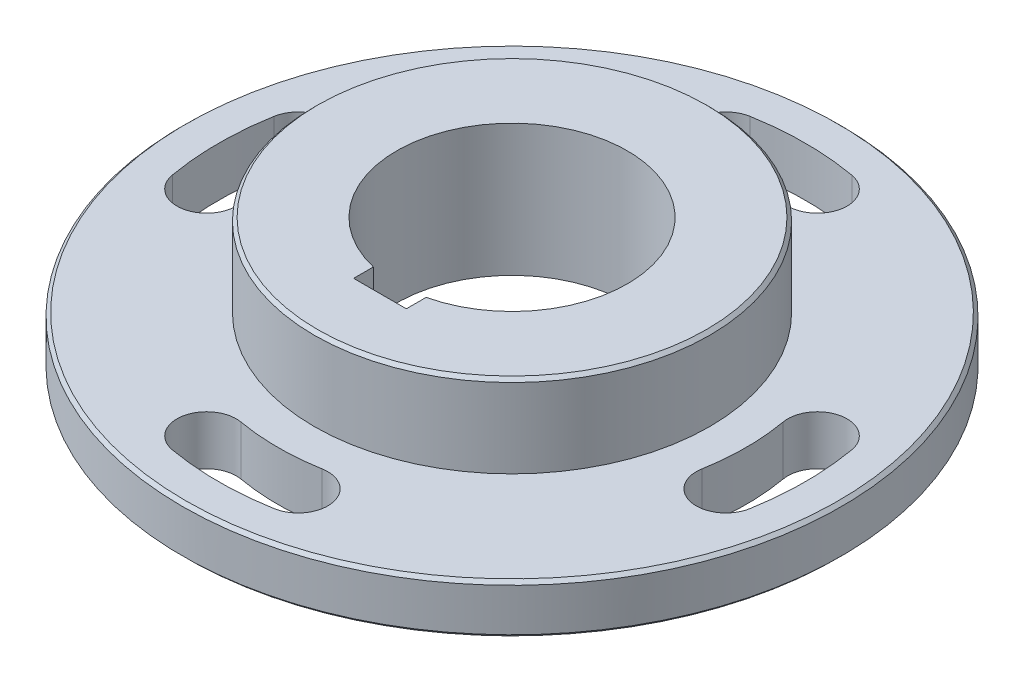
SolidWorks part; units mm, degrees
material "45"
ref_plane "前视基准面" through (0, 0, 0) normal (0, 0, 1) x (1, 0, 0)
ref_plane "上视基准面" through (0, 0, 0) normal (0, 1, 0) x (1, 0, 0)
ref_plane "右视基准面" through (0, 0, 0) normal (1, 0, 0) x (0, 0, -1)
sketch "草图1" plane through (0, 0, 0) normal (0, 0, 1) x (1, 0, 0)
  line L0 (0, 0) -> (0, 222.4832) construction
  line L1 (35, 0) -> (100, 0)
  line L2 (100, 0) -> (100, 15)
  line L3 (100, 15) -> (60, 15)
  line L4 (60, 15) -> (60, 40)
  line L5 (60, 40) -> (35, 40)
  line L6 (35, 40) -> (35, 0)
  dimension "D1" = 200
  dimension "D2" = 15
  dimension "D3" = 70
  dimension "D4" = 40
  dimension "D5" = 120
revolve "旋转1" add sketch "草图1" angle 360 about L0
sketch "草图2" plane through (0, 15, 0) normal (0, 1, 0) x (1, 0, 0)
  line L0 (0, 0) -> (0, 105.9546) construction
  line L1 (0, 0) -> (-18.9336, 107.3776) construction
  line L2 (0, 0) -> (18.7482, 106.3265) construction
  arc A0 (15.4547, 87.6479) -> (-15.4547, 87.6479) centre (0, 0) ccw
  arc A1 (12.329, 69.9214) -> (-12.329, 69.9214) centre (0, 0) ccw
  arc A2 (69.9214, -12.329) -> (87.6479, -15.4547) centre (78.7846, -13.8919) ccw
  arc A3 (69.9214, -12.329) -> (69.9214, 12.329) centre (0, 0) ccw
  arc A4 (87.6479, 15.4547) -> (69.9214, 12.329) centre (78.7846, 13.8919) ccw
  arc A5 (87.6479, -15.4547) -> (87.6479, 15.4547) centre (0, 0) ccw
  arc A6 (-12.329, -69.9214) -> (-15.4547, -87.6479) centre (-13.8919, -78.7846) ccw
  arc A7 (-12.329, -69.9214) -> (12.329, -69.9214) centre (0, 0) ccw
  arc A8 (15.4547, -87.6479) -> (12.329, -69.9214) centre (13.8919, -78.7846) ccw
  circle A9 centre (0, 0) radius 80 construction
  arc A10 (-15.4547, 87.6479) -> (-12.329, 69.9214) centre (-13.8919, 78.7846) ccw
  arc A11 (12.329, 69.9214) -> (15.4547, 87.6479) centre (13.8919, 78.7846) ccw
  arc A12 (-15.4547, -87.6479) -> (15.4547, -87.6479) centre (0, 0) ccw
  arc A13 (-69.9214, 12.329) -> (-87.6479, 15.4547) centre (-78.7846, 13.8919) ccw
  arc A14 (-69.9214, 12.329) -> (-69.9214, -12.329) centre (0, 0) ccw
  arc A15 (-87.6479, -15.4547) -> (-69.9214, -12.329) centre (-78.7846, -13.8919) ccw
  arc A16 (-87.6479, 15.4547) -> (-87.6479, -15.4547) centre (0, 0) ccw
  point P33 (0, 0)
  dimension "D1" = 18
  dimension "D2" = 4
  dimension "D3" = 10
  dimension "D5" = 160
  dimension "D4" = 10
extrude "切除-拉伸1" cut sketch "草图2" against normal through all
sketch "草图3" plane through (0, 0, 0) normal (0, -1, 0) x (1, 0, 0)
  line L0 (0, 0) -> (0, 61.6925) construction
  line L1 (-8, 40.0735) -> (8, 40.0735)
  line L2 (-8, 40.0735) -> (-8, 34.0735)
  line L3 (-8, 34.0735) -> (8, 34.0735)
  line L4 (8, 40.0735) -> (8, 34.0735)
  circle A0 centre (0, 0) radius 35 construction
  dimension "D1" = 16
  dimension "D2" = 8
  dimension "D3" = 6
extrude "切除-拉伸2" cut sketch "草图3" against normal through all
chamfer "倒角1" distance 1 angle 45 3 edges at (0, 40, -60) (0, 15, -100) (0, 0, -100)
